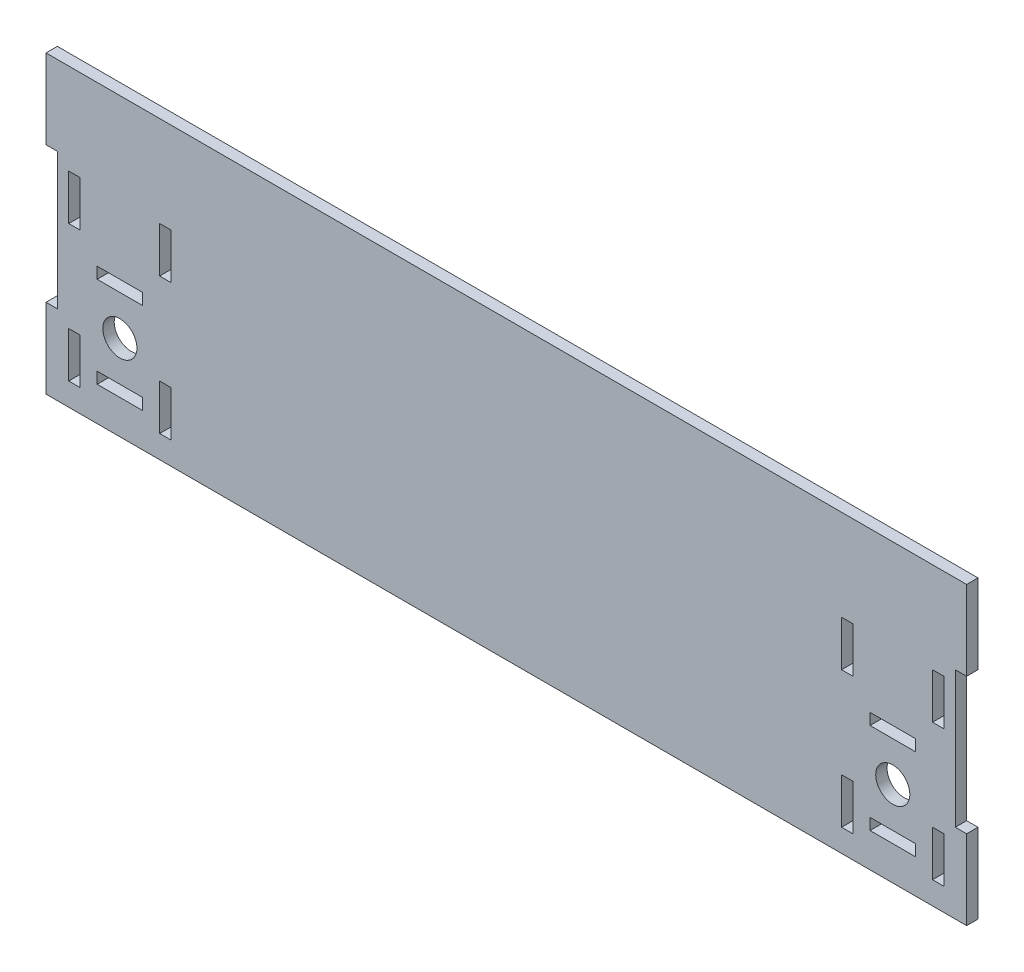
SolidWorks part; units mm, degrees
ref_plane "Front Plane" through (0, 0, 0) normal (0, 0, 1) x (1, 0, 0)
ref_plane "Top Plane" through (0, 0, 0) normal (0, 1, 0) x (1, 0, 0)
ref_plane "Right Plane" through (0, 0, 0) normal (1, 0, 0) x (0, 0, -1)
sketch "Sketch1" plane through (0, 0, 0) normal (0, 0, 1) x (1, 0, 0)
  line L1 (0, 0) -> (-405, 0)
  line L2 (0, 0) -> (0, -130)
  line L3 (0, -130) -> (-405, -130)
  line L4 (-405, 0) -> (-405, -130)
  dimension "D1" = 405
  dimension "D2" = 130
extrude "Boss-Extrude1" add sketch "Sketch1" along normal blind 5
sketch "Sketch2" plane through (0, 0, 0) normal (0, 0, -1) x (-1, 0, 0)
  line L0 (405, 0) -> (405, -130) construction
  line L1 (405, -95) -> (400, -95)
  line L2 (405, -95) -> (405, -35)
  line L3 (405, -35) -> (400, -35)
  line L4 (400, -95) -> (400, -35)
  line L5 (405, -130) -> (0, -130) construction
  line L6 (202.5, -130) -> (202.5, -95) construction
  line L7 (5, -95) -> (5, -35)
  line L8 (0, -95) -> (0, -35)
  line L9 (0, -95) -> (5, -95)
  line L10 (0, -35) -> (5, -35)
  point P6 (400, -65)
  dimension "D1" = 5
  dimension "D2" = 60
  dimension "D3" = 65
extrude "Cut-Extrude1" cut sketch "Sketch2" against normal blind 5
sketch "Sketch3" plane through (0, 0, 5) normal (0, 0, 1) x (1, 0, 0)
  line L0 (-405, -130) -> (0, -130) construction
  line L1 (-390, -120) -> (-395, -120)
  line L2 (-390, -120) -> (-390, -100)
  line L3 (-390, -100) -> (-395, -100)
  line L4 (-395, -120) -> (-395, -100)
  line L5 (-405, -95) -> (-405, -130) construction
  line L6 (-400, -35) -> (-400, -95) construction
  line L7 (-390, -40) -> (-395, -40)
  line L8 (-390, -40) -> (-390, -60)
  line L9 (-390, -60) -> (-395, -60)
  line L10 (-395, -40) -> (-395, -60)
  line L11 (-350, -40) -> (-350, -60)
  line L12 (-350, -40) -> (-355, -40)
  line L13 (-355, -40) -> (-355, -60)
  line L14 (-350, -60) -> (-355, -60)
  line L15 (-350, -120) -> (-350, -100)
  line L16 (-350, -120) -> (-355, -120)
  line L17 (-355, -120) -> (-355, -100)
  line L18 (-350, -100) -> (-355, -100)
  line L19 (-50, -120) -> (-55, -120)
  line L20 (-50, -120) -> (-50, -100)
  line L21 (-50, -100) -> (-55, -100)
  line L22 (-55, -120) -> (-55, -100)
  line L23 (-50, -40) -> (-55, -40)
  line L24 (-50, -40) -> (-50, -60)
  line L25 (-50, -60) -> (-55, -60)
  line L26 (-55, -40) -> (-55, -60)
  line L27 (-10, -40) -> (-10, -60)
  line L28 (-10, -40) -> (-15, -40)
  line L29 (-15, -40) -> (-15, -60)
  line L30 (-10, -60) -> (-15, -60)
  line L31 (-10, -120) -> (-10, -100)
  line L32 (-10, -120) -> (-15, -120)
  line L33 (-15, -120) -> (-15, -100)
  line L34 (-10, -100) -> (-15, -100)
  dimension "D1" = 20
  dimension "D2" = 5
  dimension "D3" = 10
  dimension "D4" = 10
  dimension "D5" = 5
  dimension "D6" = 20
  dimension "D7" = 5
  dimension "D8" = 40
  dimension "D9" = 2
  dimension "D10" = 2
extrude "Cut-Extrude2" cut sketch "Sketch3" against normal blind 10
sketch "Sketch4" plane through (0, 0, 5) normal (0, 0, 1) x (1, 0, 0)
  line L0 (-405, -95) -> (-405, -130) construction
  line L1 (-362.5, -115) -> (-382.5, -115)
  line L2 (-362.5, -115) -> (-362.5, -110)
  line L3 (-362.5, -110) -> (-382.5, -110)
  line L4 (-382.5, -115) -> (-382.5, -110)
  line L5 (-405, -130) -> (0, -130) construction
  line L6 (-362.5, -75) -> (-362.5, -70)
  line L7 (-362.5, -75) -> (-382.5, -75)
  line L8 (-382.5, -75) -> (-382.5, -70)
  line L9 (-362.5, -70) -> (-382.5, -70)
  line L10 (-22.5, -115) -> (-22.5, -110)
  line L11 (-22.5, -115) -> (-42.5, -115)
  line L12 (-42.5, -115) -> (-42.5, -110)
  line L13 (-22.5, -110) -> (-42.5, -110)
  line L14 (-22.5, -75) -> (-22.5, -70)
  line L15 (-22.5, -70) -> (-42.5, -70)
  line L16 (-42.5, -75) -> (-42.5, -70)
  line L17 (-22.5, -75) -> (-42.5, -75)
  dimension "D1" = 20
  dimension "D2" = 5
  dimension "D3" = 22.5
  dimension "D4" = 15
  dimension "D5" = 2
  dimension "D6" = 2
extrude "Cut-Extrude3" cut sketch "Sketch4" against normal blind 10
sketch "Sketch5" plane through (0, 0, 5) normal (0, 0, 1) x (1, 0, 0)
  line L0 (-372.5, -110) -> (-372.5, -75) construction
  line L1 (-362.5, -110) -> (-382.5, -110) construction
  line L2 (-382.5, -75) -> (-362.5, -75) construction
  line L3 (-202.5, -130) -> (-202.5, -100.7978) construction
  line L4 (-405, -130) -> (0, -130) construction
  line L5 (-32.5, -110) -> (-32.5, -75) construction
  circle A0 centre (-372.5, -92.5) radius 7.5
  circle A1 centre (-32.5, -92.5) radius 7.5
  dimension "D1" = 15
extrude "Cut-Extrude4" cut sketch "Sketch5" against normal blind 10
